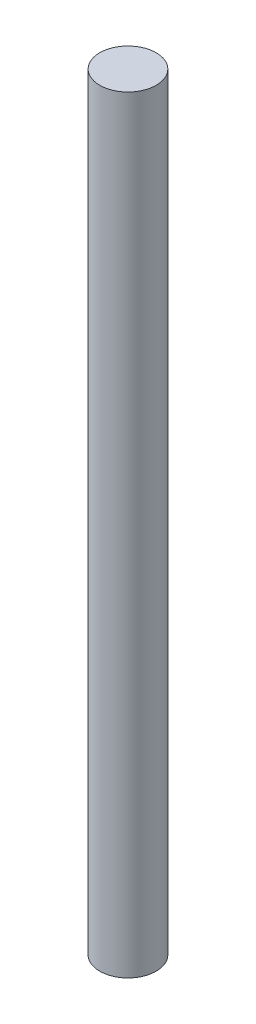
SolidWorks part; units mm, degrees
ref_plane "Front Plane" through (0, 0, 0) normal (0, 0, 1) x (1, 0, 0)
ref_plane "Top Plane" through (0, 0, 0) normal (0, 1, 0) x (1, 0, 0)
ref_plane "Right Plane" through (0, 0, 0) normal (1, 0, 0) x (0, 0, -1)
sketch "Sketch1" plane through (0, 0, 0) normal (0, 0, 1) x (1, 0, 0)
  line L5 (7.5, 204) -> (0, 204)
  line L6 (7.5, 204) -> (7.5, 0)
  line L7 (7.5, 0) -> (0, 0)
  line L8 (0, 204) -> (0, 0)
  line L9 (7.5, 204) -> (0, 0) construction
  line L10 (7.5, 0) -> (0, 204) construction
  point P0 (3.75, 102)
  dimension "D1" = 7.5
  dimension "D2" = 204
revolve "Revolve1" add sketch "Sketch1" angle 360 about L8
ref_plane "Plane1" through (0, 187, 0) normal (0, 1, 0) x (1, 0, 0)
sketch "Sketch2" plane through (0, 187, 0) normal (0, 1, 0) x (1, 0, 0)
  line L1 (1.5, 9) -> (-1.5, 9)
  line L2 (1.5, 9) -> (1.5, 6)
  line L3 (1.5, 6) -> (-1.5, 6)
  line L4 (-1.5, 9) -> (-1.5, 6)
  line L5 (1.5, 9) -> (-1.5, 6) construction
  line L6 (1.5, 6) -> (-1.5, 9) construction
  circle A0 centre (0, 0) radius 7.5 construction
  point P0 (0, 7.5)
  dimension "D1" = 3
extrude "Cut-Extrude1" cut sketch "Sketch2" against normal blind 18
ref_plane "Plane2" through (0, 104, 0) normal (0, -1, 0) x (-1, 0, 0)
sketch "Sketch3" plane through (0, 104, 0) normal (0, -1, 0) x (-1, 0, 0)
  line L1 (-1.5, 9) -> (1.5, 9)
  line L2 (-1.5, 9) -> (-1.5, 6)
  line L3 (-1.5, 6) -> (1.5, 6)
  line L4 (1.5, 9) -> (1.5, 6)
  line L5 (-1.5, 9) -> (1.5, 6) construction
  line L6 (-1.5, 6) -> (1.5, 9) construction
  circle A0 centre (0, 0) radius 7.5 construction
  point P0 (0, 7.5)
  dimension "D1" = 3
extrude "Cut-Extrude2" cut sketch "Sketch3" along normal blind 15
